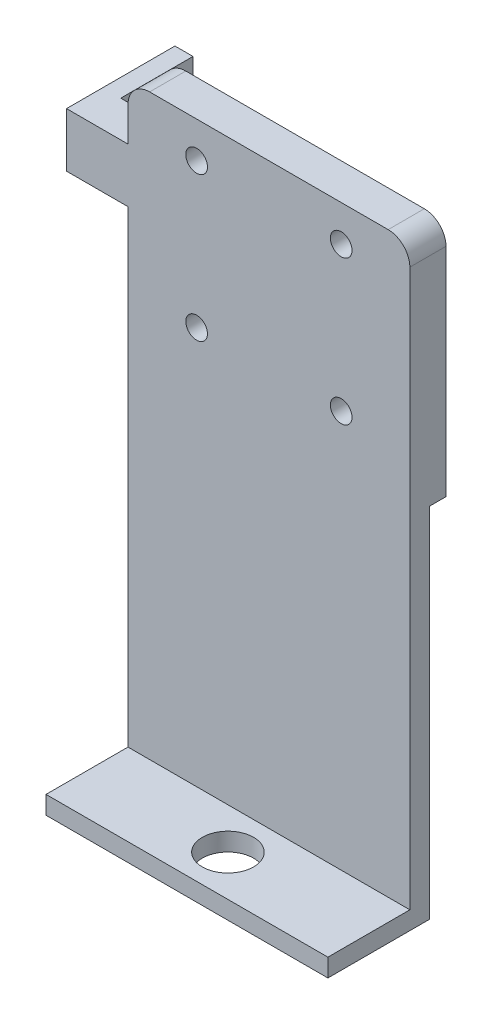
SolidWorks part; units mm, degrees
ref_plane "Alzado" through (0, 0, 0) normal (0, 0, 1) x (1, 0, 0)
ref_plane "Planta" through (0, 0, 0) normal (0, 1, 0) x (1, 0, 0)
ref_plane "Vista lateral" through (0, 0, 0) normal (1, 0, 0) x (0, 0, -1)
sketch "Croquis1" plane through (0, 0, 0) normal (0, 0, 1) x (1, 0, 0)
  line L0 (0, 0) -> (78, 0)
  line L1 (0, 0) -> (0, -15.5)
  line L2 (78, 0) -> (78, -66)
  line L3 (78, -66) -> (0, -66)
  line L4 (39, 0) -> (39, -66) construction
  line L5 (-1.9575, -10) -> (-10.5016, -10) construction
  line L6 (-1.9575, -10) -> (78, -10) construction
  line L7 (19, -10) -> (19, -50) construction
  line L8 (19, -35.7664) -> (0, -35.7664) construction
  line L9 (0, -30.5) -> (-10, -30.5)
  line L10 (-10, -30.5) -> (-17, -30.5)
  line L11 (-17, -30.5) -> (-17, -15.5)
  line L12 (-17, -15.5) -> (0, -15.5)
  line L13 (0, -30.5) -> (0, -66)
  circle A0 centre (19, -10) radius 3
  circle A1 centre (19, -50) radius 3
  circle A2 centre (59, -50) radius 3
  circle A3 centre (59, -10) radius 3
  dimension "D4" = 6
  dimension "D7" = 6
  dimension "D2" = 16
  dimension "D3" = 10
  dimension "D5" = 20
  dimension "D6" = 40
  dimension "D8" = 19
  dimension "D9" = 7
  dimension "D10" = 10
  dimension "D11" = 15
  dimension "D13" = 19
  dimension "D14" = 5.5
extrude "Saliente-Extruir1" add sketch "Croquis1" along normal blind 10
fillet "Redondeo3" radius 6 1 edges at (0, 0, 5)
fillet "Redondeo4" radius 6 1 edges at (78, 0, 5)
sketch "Croquis3" plane through (0, 0, 10) normal (0, 0, 1) x (1, 0, 0)
  line L0 (78, -66) -> (78, -165)
  line L1 (0, -66) -> (0, -165)
  line L2 (0, -165) -> (78, -165)
  line L4 (0, -66) -> (78, -66)
  circle A0 centre (59, -50) radius 3 construction
  dimension "D1" = 115
extrude "Saliente-Extruir2" add sketch "Croquis3" against normal blind 5.5 contours L4 L0 L2 L1
sketch "Croquis4" plane through (0, -165, 0) normal (0, -1, 0) x (1, 0, 0)
  line L0 (0, 10) -> (0, 32.68)
  line L1 (78, 10) -> (78, 32.68)
  line L2 (78, 32.68) -> (0, 32.68)
  line L3 (0, 10) -> (78, 10)
extrude "Saliente-Extruir3" add sketch "Croquis4" against normal blind 5 contours L3 L1 L2 L0
sketch "Croquis5" plane through (0, 0, 10) normal (0, 0, 1) x (1, 0, 0)
  line L0 (59, -50) -> (59, -165) construction
  line L1 (78, -165) -> (0, -165) construction
sketch "Croquis6" plane through (0, -160, 0) normal (0, 1, 0) x (1, 0, 0)
  line L0 (0, -32.68) -> (0, -10) construction
  line L1 (0, -21.34) -> (78, -21.34) construction
  line L2 (78, -10) -> (78, -32.68) construction
  circle A0 centre (39, -21.34) radius 7.1
  dimension "D1" = 14.2
extrude "Cortar-Extruir1" cut sketch "Croquis6" against normal blind 40 contours A0
sketch "Croquis7" plane through (-17, 0, 0) normal (-1, 0, 0) x (0, 0, 1)
  line L0 (0, -15.5) -> (-20, -15.5)
  line L1 (0, -30.5) -> (-20, -30.5)
  line L2 (-20, -30.5) -> (-20, -15.5)
  line L3 (0, -15.5) -> (0, -30.5)
  dimension "D1" = 20
extrude "Saliente-Extruir4" add sketch "Croquis7" against normal blind 5
